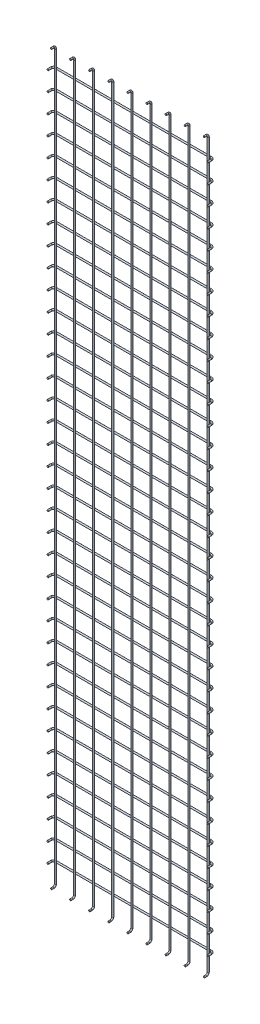
SolidWorks part; units mm, degrees
material "AISI 1020"
ref_plane "Спереди" through (0, 0, 0) normal (0, 0, 1) x (1, 0, 0)
ref_plane "Сверху" through (0, 0, 0) normal (0, 1, 0) x (1, 0, 0)
ref_plane "Справа" through (0, 0, 0) normal (1, 0, 0) x (0, 0, -1)
sketch "Эскиз1" plane through (0, 0, 0) normal (1, 0, 0) x (0, 0, -1)
  line L0 (-11, 953) -> (-6, 953)
  line L1 (0, 947) -> (0, -947)
  line L2 (-6, -953) -> (-11, -953)
  line L3 (-11, -955) -> (-11, 955) construction
  line L4 (12, -955) -> (-12, -955) construction
  line L5 (-12, 955) -> (12, 955) construction
  arc A0 (0, -947) -> (-6, -953) centre (-6, -947) cw
  arc A1 (-6, 953) -> (0, 947) centre (-6, 947) cw
  point P10 (0, 0)
  dimension "D3" = 6
  dimension "D1" = 2
  dimension "D2" = 2
ref_plane "Плоскость1" through (0, 0, 11) normal (0, 0, 1) x (1, 0, 0)
sketch "Эскиз2" plane through (0, 0, 11) normal (0, 0, 1) x (1, 0, 0)
  line L0 (0, -953) -> (0, -947) construction
  circle A0 centre (0, -953) radius 2
  point P4 (0, -951.8757)
  dimension "D1" = 4
sweep "По траектории1" add profiles "Эскиз2" path "Эскиз1"
pattern_linear "Линейный массив1" count 5 spacing 50 along (-1, 0, 0) of bodies 103
mirror "Зеркальное отражение1" about plane through (0, 0, 0) normal (1, 0, 0) of bodies 107 106 105 104
sketch "Эскиз3" plane through (0, 0, 0) normal (0, 1, 0) x (1, 0, 0)
  line L0 (-209.25, -11) -> (-209.25, -2)
  line L2 (-203.25, 4) -> (203.25, 4)
  line L3 (209.25, -2) -> (209.25, -11)
  line L4 (-13.2, -11) -> (13.2, -11) construction
  line L5 (211.25, 12) -> (211.25, -12) construction
  line L6 (-211.25, -12) -> (-211.25, 12) construction
  arc A0 (203.25, 4) -> (209.25, -2) centre (203.25, -2) cw
  arc A1 (-209.25, -2) -> (-203.25, 4) centre (-203.25, -2) cw
  circle A2 centre (200, 0) radius 2 construction
  point P2 (0, 0)
  point P12 (0, 0)
  dimension "D3" = 6
  dimension "D4" = 2
  dimension "D1" = 2
  dimension "D2" = 2
sketch "Эскиз4" plane through (0, 0, 11) normal (0, 0, 1) x (1, 0, 0)
  circle A0 centre (-209.25, 0) radius 2
  dimension "D1" = 4
sweep "По траектории2" add profiles "Эскиз4" path "Эскиз3"
pattern_linear "Линейный массив7" count 19 spacing 50 along (0, -1, 0) of "По траектории2"
pattern_linear "Линейный массив8" count 19 spacing 50 along (0, 1, 0) of "По траектории2"
